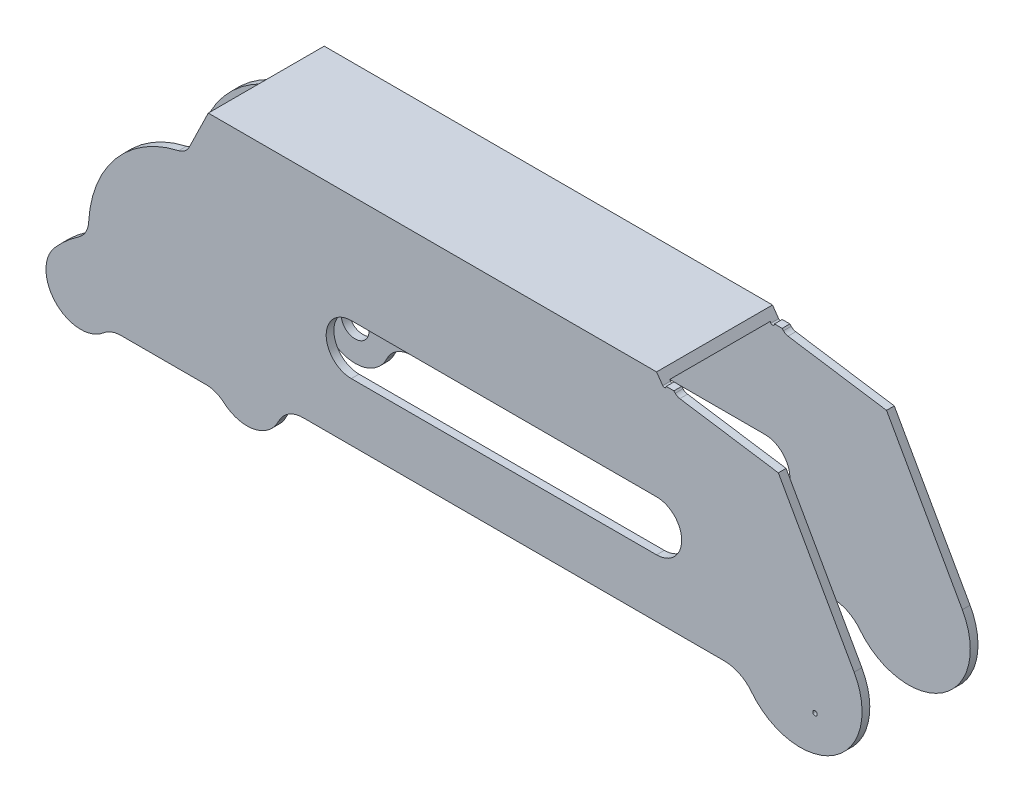
SolidWorks part; units mm, degrees
ref_plane "Front Plane" through (0, 0, 0) normal (0, 0, 1) x (1, 0, 0)
ref_plane "Top Plane" through (0, 0, 0) normal (0, 1, 0) x (1, 0, 0)
ref_plane "Right Plane" through (0, 0, 0) normal (1, 0, 0) x (0, 0, -1)
ref_plane "Plane1" through (0, 0, -13) normal (0, 0, 1) x (1, 0, 0)
sketch "Sketch1" plane through (0, 0, -13) normal (0, 0, 1) x (1, 0, 0)
  line L0 (38.5895, 53.7145) -> (38.391, 54)
  line L1 (38.391, 54) -> (37, 56)
  line L2 (37, 56) -> (-79, 56)
  line L3 (-79, 56) -> (-84.7975, 44.1133)
  line L4 (-104.6118, -5.1396) -> (-76.5112, -5.1396)
  line L5 (-59.8988, 0) -> (59.5208, 0)
  line L6 (88.1191, 14.2695) -> (68.5078, 49.132)
  line L7 (68.5078, 49.132) -> (42.3085, 53.1133)
  line L8 (42.3085, 53.1133) -> (41.5, 54)
  line L9 (41.5, 54) -> (39.5, 54)
  arc A0 (39.5, 54) -> (38.5895, 53.7145) centre (39, 54) cw
  arc A1 (-84.7975, 44.1133) -> (-109.9611, 13.0525) centre (-79.9961, 14.5) ccw
  arc A2 (-109.9611, 13.0525) -> (-118.8226, 5.8696) centre (-94.5644, -15) ccw
  arc A3 (-118.8226, 5.8696) -> (-104.6118, -5.1396) centre (-112, 0) ccw
  arc A4 (-76.5112, -5.1396) -> (-59.8988, 0) centre (-69, 0) ccw
  arc A5 (59.5208, 0) -> (88.1191, 14.2695) centre (74.1741, 6.4249) ccw
extrude "Boss-Extrude1" add sketch "Sketch1" against normal blind 2
sketch "Sketch2" plane through (0, 0, -13) normal (0, 0, 1) x (1, 0, 0)
  line L0 (37, 56) -> (38.391, 54)
  line L1 (38.391, 54) -> (-79.9755, 54)
  line L2 (-79.9755, 54) -> (-79, 56)
  line L3 (-79, 56) -> (37, 56)
extrude "Boss-Extrude2" add sketch "Sketch2" along normal blind 26
sketch "Sketch3" plane through (0, 0, 13) normal (0, 0, 1) x (1, 0, 0)
  line L0 (39.5, 54) -> (41.5, 54)
  line L1 (41.5, 54) -> (42.3085, 53.1133)
  line L2 (42.3085, 53.1133) -> (68.5078, 49.132)
  line L3 (68.5078, 49.132) -> (88.1191, 14.2695)
  line L4 (59.5208, 0) -> (-59.8988, 0)
  line L5 (-76.5112, -5.1396) -> (-104.6118, -5.1396)
  line L6 (-84.7975, 44.1133) -> (-79, 56)
  line L7 (-79, 56) -> (37, 56)
  line L8 (37, 56) -> (38.5893, 53.7148)
  arc A0 (38.5893, 53.7148) -> (39.5, 54) centre (39, 54) ccw
  arc A1 (88.1191, 14.2695) -> (59.5208, 0) centre (74.1741, 6.4249) cw
  arc A2 (-59.8988, 0) -> (-76.5112, -5.1396) centre (-69, 0) cw
  arc A3 (-104.6118, -5.1396) -> (-118.8226, 5.8696) centre (-112, 0) cw
  arc A4 (-118.8226, 5.8696) -> (-109.9611, 13.0525) centre (-94.5644, -15) cw
  arc A5 (-109.9611, 13.0525) -> (-84.7975, 44.1133) centre (-79.9961, 14.5) cw
extrude "Boss-Extrude3" add sketch "Sketch3" along normal blind 2
sketch "Sketch4" plane through (0, 0, -15) normal (0, 0, -1) x (-1, 0, 0)
  line L0 (-37, 15) -> (42, 15)
  line L1 (42, 28) -> (-37, 28)
  arc A0 (-37, 28) -> (-37, 15) centre (-37, 21.5) ccw
  arc A1 (42, 15) -> (42, 28) centre (42, 21.5) ccw
extrude "Cut-Extrude1" cut sketch "Sketch4" against normal up to next
sketch "Sketch5" plane through (0, 0, 15) normal (0, 0, 1) x (1, 0, 0)
  line L0 (37, 28) -> (-42, 28)
  line L1 (-42, 15) -> (37, 15)
  arc A0 (-42, 28) -> (-42, 15) centre (-42, 21.5) ccw
  arc A1 (37, 15) -> (37, 28) centre (37, 21.5) ccw
extrude "Cut-Extrude2" cut sketch "Sketch5" against normal through all
hole_wizard "Hole1" positions "Sketch7" profile "Sketch6" legacy
sketch "Sketch7" plane through (0, 0, 13) normal (0, 0, -1) x (-1, 0, 0)
  point P0 (-78.0002, 0)
sketch "Sketch6" plane through (78.0002, 0, 13) normal (1, 0, 0) x (0, 1, 0)
  line L0 (0, 0) -> (0, 2)
  line L1 (0, 2) -> (0.5784, 2)
  line L2 (0.5784, 2) -> (0.5784, 0)
  line L3 (0.5784, 0) -> (0, 0)
  line L4 (0, 110) -> (0, -10) construction
  dimension "Diameter" = 1.1567
  dimension "Depth" = 2
hole_wizard "Hole2" positions "Sketch9" profile "Sketch8" legacy
sketch "Sketch9" plane through (0, 0, -13) normal (0, 0, 1) x (1, 0, 0)
  point P0 (-69, 0)
sketch "Sketch8" plane through (-69, 0, -13) normal (1, 0, 0) x (0, -1, 0)
  line L0 (0, 0) -> (0, 2)
  line L1 (0, 2) -> (3.6164, 2)
  line L2 (3.6164, 2) -> (3.6164, 0)
  line L3 (3.6164, 0) -> (0, 0)
  line L4 (0, 110) -> (0, -10) construction
  dimension "Diameter" = 7.2329
  dimension "Depth" = 2
fillet "Fillet1" radius 2 2 edges at (42.3085, 53.1133, 14) (42.3085, 53.1133, -14)
fillet "Fillet2" radius 4 2 edges at (-84.7975, 44.1133, 14) (-84.7975, 44.1133, -14)
fillet "Fillet3" radius 6 2 edges at (-109.9611, 13.0525, 14) (-109.9611, 13.0525, -14)
fillet "Fillet4" radius 7 6 edges at (-76.5112, -5.1396, 14) (-59.8988, 0, 14) (-104.6118, -5.1396, 14) (-59.8988, 0, -14) (-76.5112, -5.1396, -14) (-104.6118, -5.1396, -14)
fillet "Fillet5" radius 9 2 edges at (59.5208, 0, 14) (59.5208, 0, -14)
sketch "Sketch10" plane through (0, 0, -15) normal (0, 0, -1) x (-1, 0, 0)
  circle A0 centre (112.1172, 0) radius 4.3678
